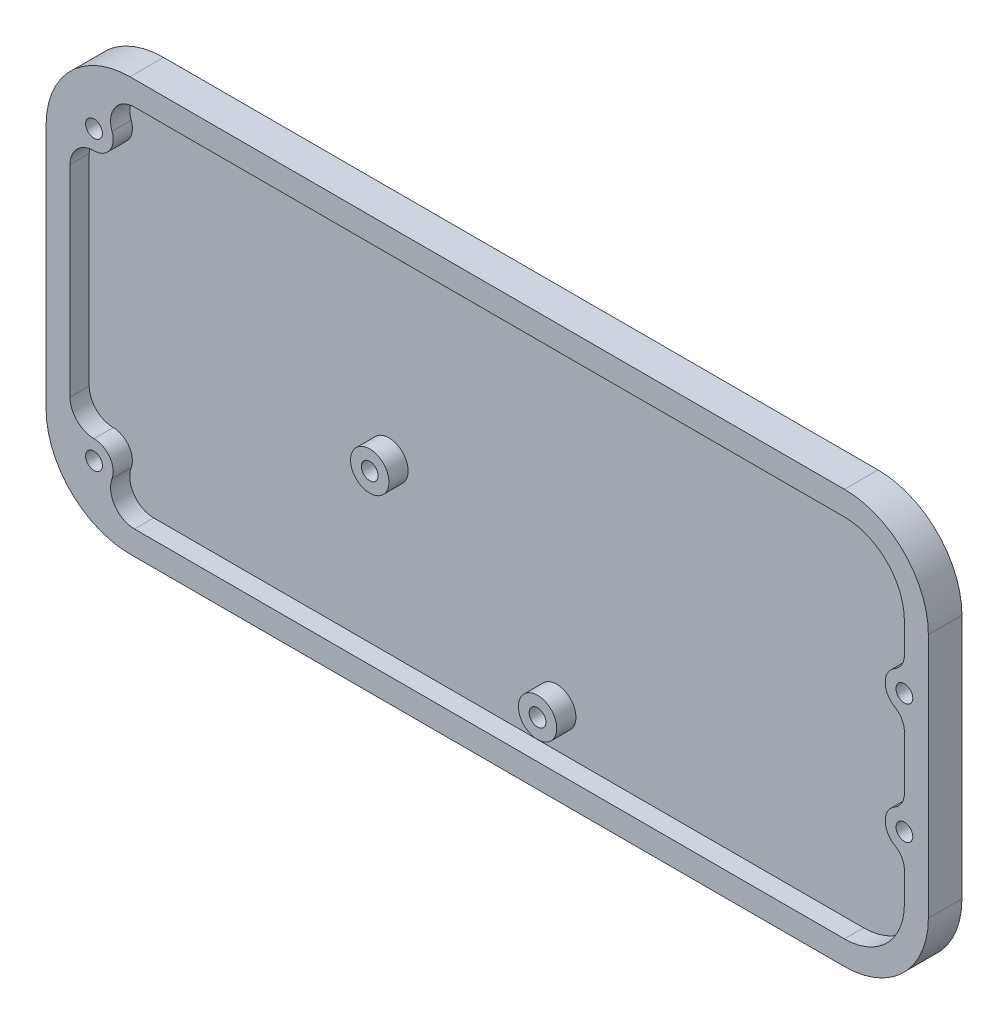
SolidWorks part; units mm, degrees
ref_plane "Alzado" through (0, 0, 0) normal (0, 0, 1) x (1, 0, 0)
ref_plane "Planta" through (0, 0, 0) normal (0, 1, 0) x (1, 0, 0)
ref_plane "Vista lateral" through (0, 0, 0) normal (1, 0, 0) x (0, 0, -1)
sketch "Croquis1" plane through (0, 0, 0) normal (0, 0, 1) x (1, 0, 0)
  line L1 (17.5, 0) -> (166.5, 0)
  line L2 (0, 17.5) -> (0, 68.7)
  line L3 (17.5, 86.2) -> (166.5, 86.2)
  line L4 (184, 17.5) -> (184, 68.7)
  arc A0 (166.5, 86.2) -> (184, 68.7) centre (166.5, 68.7) cw
  arc A1 (166.5, 0) -> (184, 17.5) centre (166.5, 17.5) ccw
  arc A2 (17.5, 0) -> (0, 17.5) centre (17.5, 17.5) cw
  arc A3 (0, 68.7) -> (17.5, 86.2) centre (17.5, 68.7) cw
  point P9 (184, 0)
  point P12 (0, 0)
  point P15 (0, 86.2)
  dimension "D3" = 17.5
  dimension "D1" = 184
  dimension "D2" = 86.2
extrude "Saliente-Extruir1" add sketch "Croquis1" along normal blind 3
sketch "Croquis2" plane through (0, 0, 3) normal (0, 0, 1) x (1, 0, 0)
  line L0 (5, 68.7) -> (5, 17.5) construction
  line L1 (18.4493, 5) -> (166.5, 5)
  line L2 (179, 17.5) -> (179, 23.6718)
  line L3 (166.5, 81.2) -> (17.5, 81.2)
  line L4 (166.5, 86.2) -> (17.5, 86.2)
  line L5 (0, 68.7) -> (0, 17.5)
  line L6 (17.5, 0) -> (166.5, 0)
  line L7 (184, 17.5) -> (184, 68.7)
  line L8 (166.5, 86.2) -> (17.5, 86.2)
  line L9 (0, 68.7) -> (0, 17.5)
  line L10 (17.5, 0) -> (166.5, 0)
  line L11 (184, 17.5) -> (184, 68.7)
  line L12 (10, 73.1) -> (10, 13.1) construction
  line L13 (10, 43.1) -> (5, 43.1) construction
  line L14 (5, 22.1) -> (5, 64.1)
  line L15 (17.5, 5) -> (166.5, 5) construction
  line L16 (179, 37.5282) -> (179, 48.6718)
  line L17 (179, 62.5282) -> (179, 68.7)
  line L18 (179, 17.5) -> (179, 68.7) construction
  arc A1 (166.5, 5) -> (179, 17.5) centre (166.5, 17.5) ccw
  arc A2 (179, 68.7) -> (166.5, 81.2) centre (166.5, 68.7) ccw
  arc A4 (184, 68.7) -> (166.5, 86.2) centre (166.5, 68.7) ccw
  arc A5 (17.5, 86.2) -> (0, 68.7) centre (17.5, 68.7) ccw
  arc A6 (0, 17.5) -> (17.5, 0) centre (17.5, 17.5) ccw
  arc A7 (166.5, 0) -> (184, 17.5) centre (166.5, 17.5) ccw
  arc A8 (184, 68.7) -> (166.5, 86.2) centre (166.5, 68.7) ccw
  arc A9 (17.5, 86.2) -> (0, 68.7) centre (17.5, 68.7) ccw
  arc A10 (0, 17.5) -> (17.5, 0) centre (17.5, 17.5) ccw
  arc A11 (166.5, 0) -> (184, 17.5) centre (166.5, 17.5) ccw
  circle A12 centre (102.5, 13) radius 4
  circle A13 centre (67.5, 40) radius 4
  arc A14 (10, 69.1) -> (13.7552, 74.4778) centre (10, 73.1) ccw
  arc A15 (13.7552, 11.7222) -> (10, 17.1) centre (10, 13.1) ccw
  arc A16 (177, 34.0641) -> (177, 27.1359) centre (179, 30.6) ccw
  arc A17 (177, 59.0641) -> (177, 52.1359) centre (179, 55.6) ccw
  arc A18 (5, 64.1) -> (10, 69.1) centre (10, 64.1) cw
  arc A19 (13.7552, 74.4778) -> (18.4493, 81.2) centre (18.4493, 76.2) cw
  arc A20 (13.7552, 11.7222) -> (18.4493, 5) centre (18.4493, 10) ccw
  arc A21 (17.5, 81.2) -> (5, 68.7) centre (17.5, 68.7) ccw construction
  arc A22 (5, 22.1) -> (10, 17.1) centre (10, 22.1) ccw
  arc A23 (177, 27.1359) -> (179, 23.6718) centre (175, 23.6718) cw
  arc A24 (5, 17.5) -> (17.5, 5) centre (17.5, 17.5) ccw construction
  arc A25 (179, 37.5282) -> (177, 34.0641) centre (175, 37.5282) cw
  arc A26 (177, 52.1359) -> (179, 48.6718) centre (175, 48.6718) cw
  arc A27 (179, 62.5282) -> (177, 59.0641) centre (175, 62.5282) cw
  point P24 (10, 73.1)
  point P25 (10, 13.1)
  point P26 (67.5, 40)
  point P27 (102.5, 13)
  point P28 (179, 55.6)
  point P29 (179, 30.6)
  point P68 (176.8689, 58.985)
  dimension "D12" = 8
  dimension "D3" = 67.5
  dimension "D4" = 102.5
  dimension "D5" = 179
  dimension "D6" = 13
  dimension "D7" = 30.6
  dimension "D8" = 40
  dimension "D9" = 55.6
  dimension "D10" = 60
  dimension "D11" = 10
  dimension "D1" = 0
  dimension "D2" = 5
extrude "Saliente-Extruir3" add sketch "Croquis2" along normal blind 4
sketch "Croquis3" plane through (0, 0, 7) normal (0, 0, 1) x (1, 0, 0)
  circle A0 centre (10, 13.1) radius 1.75
  circle A1 centre (67.5, 40) radius 1.75
  circle A2 centre (102.5, 13) radius 1.75
  circle A3 centre (10, 73.1) radius 1.75
  circle A4 centre (179, 55.6) radius 1.75
  circle A5 centre (179, 30.6) radius 1.75
  dimension "D1" = 3.5
extrude "Cortar-Extruir1" cut sketch "Croquis3" against normal through all both and the other way through all
sketch "Croquis4" plane through (0, 0, 0) normal (0, 0, -1) x (-1, 0, 0)
  circle A0 centre (-179, 30.6) radius 3
  circle A1 centre (-179, 55.6) radius 3
  circle A2 centre (-102.5, 13) radius 3
  circle A3 centre (-67.5, 40) radius 3
  circle A4 centre (-10, 73.1) radius 3
  circle A5 centre (-10, 13.1) radius 3
  dimension "D1" = 6
extrude "Cortar-Extruir2" cut sketch "Croquis4" against normal blind 3
